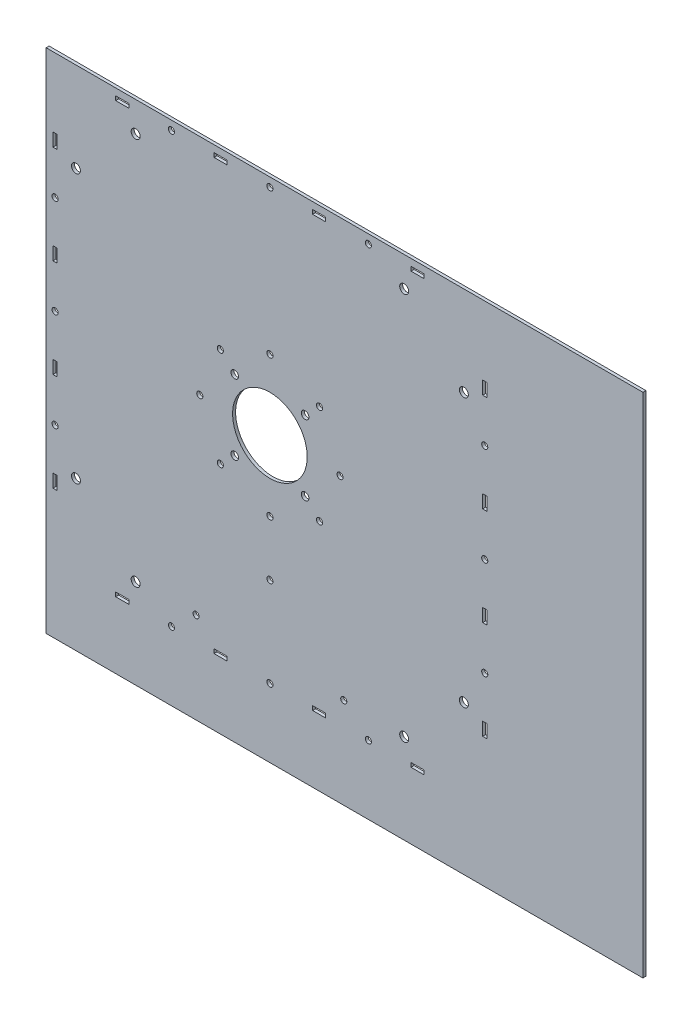
SolidWorks part; units mm, degrees
ref_plane "前视基准面" through (0, 0, 0) normal (0, 0, 1) x (1, 0, 0)
ref_plane "上视基准面" through (0, 0, 0) normal (0, 1, 0) x (1, 0, 0)
ref_plane "右视基准面" through (0, 0, 0) normal (1, 0, 0) x (0, 0, -1)
sketch "草图1" plane through (0, 0, 0) normal (0, 0, 1) x (1, 0, 0)
  line L0 (1.4571, -21.1871) -> (1.4571, -41.1871) construction
  line L2 (1.4571, -21.1871) -> (1.4571, 44.8129) construction
  line L4 (151.4571, -41.1871) -> (151.4571, 108.8129)
  line L5 (151.4571, 108.8129) -> (-148.5429, 108.8129)
  line L6 (-148.5429, 108.8129) -> (-148.5429, -191.1871)
  line L7 (-148.5429, -191.1871) -> (151.4571, -191.1871)
  line L8 (151.4571, -191.1871) -> (151.4571, -41.1871)
  line L9 (-148.5429, -41.1871) -> (-161.9412, -41.1871) construction
  line L10 (1.4571, -191.1871) -> (1.4571, -181.0361) construction
  circle A6 centre (1.4571, -21.1871) radius 241.4173 construction
  circle A9 centre (1.4571, -41.1871) radius 25
  circle A10 centre (25.0271, -17.6171) radius 2.55
  circle A11 centre (25.0271, -64.7571) radius 2.55
  circle A12 centre (-22.1129, -64.7571) radius 2.55
  circle A13 centre (-22.1129, -17.6171) radius 2.55
  circle A14 centre (115.1844, -53.0393) radius 12.2821 construction
  dimension "D1" = 50
  dimension "D4" = 5.1
  dimension "D2" = 300
  dimension "D3" = 300
  dimension "D5" = 23.57
  dimension "D6" = 23.57
  dimension "D7" = 4
extrude "凸台-拉伸1" add sketch "草图1" along normal blind 2
sketch "草图3" plane through (0, 0, 2) normal (0, 0, 1) x (1, 0, 0)
  line L1 (96.0571, -183.7871) -> (104.8571, -183.7871)
  line L13 (1.4571, -191.1871) -> (1.4571, -185.1871) construction
  line L14 (-148.5429, -191.1871) -> (151.4571, -191.1871) construction
  line L15 (1.4571, -185.1871) -> (34.4571, -185.1871) construction
  line L16 (34.4571, -185.1871) -> (67.4571, -185.1871) construction
  line L17 (30.0571, -183.7871) -> (38.8571, -183.7871)
  line L18 (30.0571, -183.7871) -> (30.0571, -186.5871)
  line L19 (30.0571, -186.5871) -> (38.8571, -186.5871)
  line L20 (38.8571, -183.7871) -> (38.8571, -186.5871)
  line L21 (30.0571, -183.7871) -> (38.8571, -186.5871) construction
  line L22 (30.0571, -186.5871) -> (38.8571, -183.7871) construction
  line L23 (67.4571, -185.1871) -> (100.4571, -185.1871) construction
  line L24 (96.0571, -183.7871) -> (96.0571, -186.5871)
  line L25 (96.0571, -186.5871) -> (104.8571, -186.5871)
  line L26 (96.0571, -186.5871) -> (104.8571, -183.7871) construction
  line L27 (104.8571, -186.5871) -> (104.8571, -183.7871)
  line L28 (-35.9429, -183.7871) -> (-35.9429, -186.5871)
  line L29 (-27.1429, -183.7871) -> (-35.9429, -183.7871)
  line L30 (-27.1429, -183.7871) -> (-27.1429, -186.5871)
  line L31 (-27.1429, -186.5871) -> (-35.9429, -186.5871)
  line L32 (-93.1429, -183.7871) -> (-93.1429, -186.5871)
  line L33 (-101.9429, -186.5871) -> (-101.9429, -183.7871)
  line L34 (-93.1429, -183.7871) -> (-101.9429, -183.7871)
  line L35 (-93.1429, -186.5871) -> (-101.9429, -186.5871)
  line L36 (-141.1429, 53.4129) -> (-141.1429, 62.2129)
  line L37 (-143.9429, 53.4129) -> (-143.9429, 62.2129)
  line L38 (-143.9429, 62.2129) -> (-141.1429, 62.2129)
  line L39 (-141.1429, 53.4129) -> (-143.9429, 53.4129)
  line L40 (-141.1429, -12.5871) -> (-141.1429, -3.7871)
  line L41 (-141.1429, -3.7871) -> (-143.9429, -3.7871)
  line L42 (-143.9429, -12.5871) -> (-143.9429, -3.7871)
  line L43 (-141.1429, -12.5871) -> (-143.9429, -12.5871)
  line L44 (-141.1429, -69.7871) -> (-143.9429, -69.7871)
  line L45 (-141.1429, -69.7871) -> (-141.1429, -78.5871)
  line L46 (-143.9429, -69.7871) -> (-143.9429, -78.5871)
  line L47 (-141.1429, -78.5871) -> (-143.9429, -78.5871)
  line L48 (-141.1429, -135.7871) -> (-141.1429, -144.5871)
  line L49 (-143.9429, -135.7871) -> (-143.9429, -144.5871)
  line L50 (-141.1429, -135.7871) -> (-143.9429, -135.7871)
  line L51 (-143.9429, -144.5871) -> (-141.1429, -144.5871)
  line L52 (96.0571, 101.4129) -> (104.8571, 101.4129)
  line L53 (96.0571, 104.2129) -> (104.8571, 104.2129)
  line L54 (104.8571, 104.2129) -> (104.8571, 101.4129)
  line L55 (96.0571, 101.4129) -> (96.0571, 104.2129)
  line L56 (30.0571, 101.4129) -> (38.8571, 101.4129)
  line L57 (38.8571, 101.4129) -> (38.8571, 104.2129)
  line L58 (30.0571, 104.2129) -> (38.8571, 104.2129)
  line L59 (30.0571, 101.4129) -> (30.0571, 104.2129)
  line L60 (-27.1429, 101.4129) -> (-27.1429, 104.2129)
  line L61 (-27.1429, 101.4129) -> (-35.9429, 101.4129)
  line L62 (-27.1429, 104.2129) -> (-35.9429, 104.2129)
  line L63 (-35.9429, 101.4129) -> (-35.9429, 104.2129)
  line L64 (-93.1429, 101.4129) -> (-101.9429, 101.4129)
  line L65 (-93.1429, 104.2129) -> (-101.9429, 104.2129)
  line L66 (-93.1429, 101.4129) -> (-93.1429, 104.2129)
  line L67 (-101.9429, 104.2129) -> (-101.9429, 101.4129)
  line L68 (144.0571, -135.7871) -> (144.0571, -144.5871)
  line L69 (146.8571, -135.7871) -> (146.8571, -144.5871)
  line L70 (146.8571, -144.5871) -> (144.0571, -144.5871)
  line L71 (144.0571, -135.7871) -> (146.8571, -135.7871)
  line L72 (144.0571, -69.7871) -> (144.0571, -78.5871)
  line L73 (144.0571, -78.5871) -> (146.8571, -78.5871)
  line L74 (146.8571, -69.7871) -> (146.8571, -78.5871)
  line L75 (144.0571, -69.7871) -> (146.8571, -69.7871)
  line L76 (144.0571, -12.5871) -> (146.8571, -12.5871)
  line L77 (144.0571, -12.5871) -> (144.0571, -3.7871)
  line L78 (146.8571, -12.5871) -> (146.8571, -3.7871)
  line L79 (144.0571, -3.7871) -> (146.8571, -3.7871)
  line L80 (144.0571, 53.4129) -> (144.0571, 62.2129)
  line L81 (146.8571, 53.4129) -> (146.8571, 62.2129)
  line L82 (144.0571, 53.4129) -> (146.8571, 53.4129)
  line L83 (146.8571, 62.2129) -> (144.0571, 62.2129)
  line L84 (50.9571, -185.1871) -> (50.9571, -170.1871) construction
  line L85 (17.9571, -185.1871) -> (17.9571, -170.1871) construction
  line L86 (-48.0429, -170.1871) -> (-15.0429, -170.1871) construction
  line L91 (-31.5429, -170.1871) -> (-31.5429, -155.1871) construction
  line L92 (100.4571, -185.1871) -> (104.8571, -186.5871) construction
  line L93 (-31.5429, -155.1871) -> (1.4571, -155.1871) construction
  line L95 (1.4571, -155.1871) -> (34.4571, -155.1871) construction
  circle A0 centre (1.4571, -185.1871) radius 2.05
  circle A1 centre (67.4571, -185.1871) radius 2.05
  circle A2 centre (-64.5429, -185.1871) radius 2.05
  circle A3 centre (-142.5429, 24.8129) radius 2.05
  circle A4 centre (-142.5429, -41.1871) radius 2.05
  circle A5 centre (-142.5429, -107.1871) radius 2.05
  circle A6 centre (67.4571, 102.8129) radius 2.05
  circle A7 centre (1.4571, 102.8129) radius 2.05
  circle A8 centre (-64.5429, 102.8129) radius 2.05
  circle A9 centre (145.4571, -107.1871) radius 2.05
  circle A10 centre (145.4571, -41.1871) radius 2.05
  circle A11 centre (145.4571, 24.8129) radius 2.05
  circle A15 centre (17.9571, -170.1871) radius 2 construction
  circle A16 centre (-15.0429, -170.1871) radius 2 construction
  circle A17 centre (50.9571, -170.1871) radius 2.05
  circle A18 centre (-48.0429, -170.1871) radius 2.05
  circle A19 centre (-31.5429, -155.1871) radius 2.05 construction
  circle A20 centre (34.4571, -155.1871) radius 2.05 construction
  circle A22 centre (1.4571, -155.1871) radius 2 construction
  circle A23 centre (1.4571, -41.1871) radius 47 construction
  circle A24 centre (1.4571, -88.1871) radius 2.05
  circle A25 centre (-31.7769, -74.4212) radius 2.05
  circle A26 centre (-45.5429, -41.1871) radius 2.05
  circle A27 centre (-31.7769, -7.9531) radius 2.05
  circle A28 centre (1.4571, 5.8129) radius 2.05
  circle A29 centre (34.6912, -7.9531) radius 2.05
  circle A30 centre (48.4571, -41.1871) radius 2.05
  circle A31 centre (34.6912, -74.4212) radius 2.05
  circle A32 centre (1.4571, -125.1871) radius 2.05
  dimension "D1" = 8.8
  dimension "D3" = 4
  dimension "D4" = 8
  dimension "D5" = 30
  dimension "D6" = 4.1
  dimension "D7" = 94
  dimension "D8" = 4.1
  dimension "D9" = 8.8
  dimension "D2" = 2.8
  dimension "D10" = 2.8
extrude "切除-拉伸2" cut sketch "草图3" against normal blind 4
sketch "草图6" plane through (0, 0, 2) normal (0, 0, 1) x (1, 0, 0)
sketch "草图7" plane through (0, 0, 2) normal (0, 0, 1) x (1, 0, 0)
  line L5 (-148.5429, -171.1871) -> (151.4571, -171.1871) construction
  line L6 (-148.5429, 108.8129) -> (-148.5429, -191.1871) construction
  line L7 (151.4571, -191.1871) -> (151.4571, 108.8129) construction
  line L8 (-148.5429, -191.1871) -> (151.4571, -191.1871) construction
  circle A0 centre (-88.5429, -171.1871) radius 3
  circle A1 centre (91.4571, -171.1871) radius 3
  circle A2 centre (-128.5429, 48.8129) radius 3
  circle A3 centre (-128.5429, -131.1871) radius 3
  circle A4 centre (91.4571, 88.8129) radius 3
  circle A5 centre (-88.5429, 88.8129) radius 3
  circle A6 centre (131.4571, -131.1871) radius 3
  circle A7 centre (131.4571, 48.8129) radius 3
  dimension "D2" = 6
  dimension "D4" = 60
  dimension "D1" = 20
  dimension "D3" = 60
  dimension "D5" = 4
extrude "切除-拉伸3" cut sketch "草图7" against normal blind 10
sketch "草图9" plane through (0, 0, 2) normal (0, 0, 1) x (1, 0, 0)
  line L0 (151.4571, 108.8129) -> (251.4571, 108.8129)
  line L1 (151.4571, -191.1871) -> (251.4571, -191.1871) construction
  line L2 (251.4571, -191.1871) -> (251.4571, 108.8129)
  line L3 (151.4571, 108.8129) -> (151.4571, -191.1871)
  line L4 (-148.5429, -191.1871) -> (-148.5429, -231.1871)
  line L5 (-148.5429, -231.1871) -> (251.4571, -231.1871)
  line L6 (251.4571, -231.1871) -> (251.4571, -191.1871)
  line L7 (-148.5429, -191.1871) -> (151.4571, -191.1871)
  dimension "D1" = 100
  dimension "D2" = 40
extrude "凸台-拉伸3" add sketch "草图9" against normal blind 2
